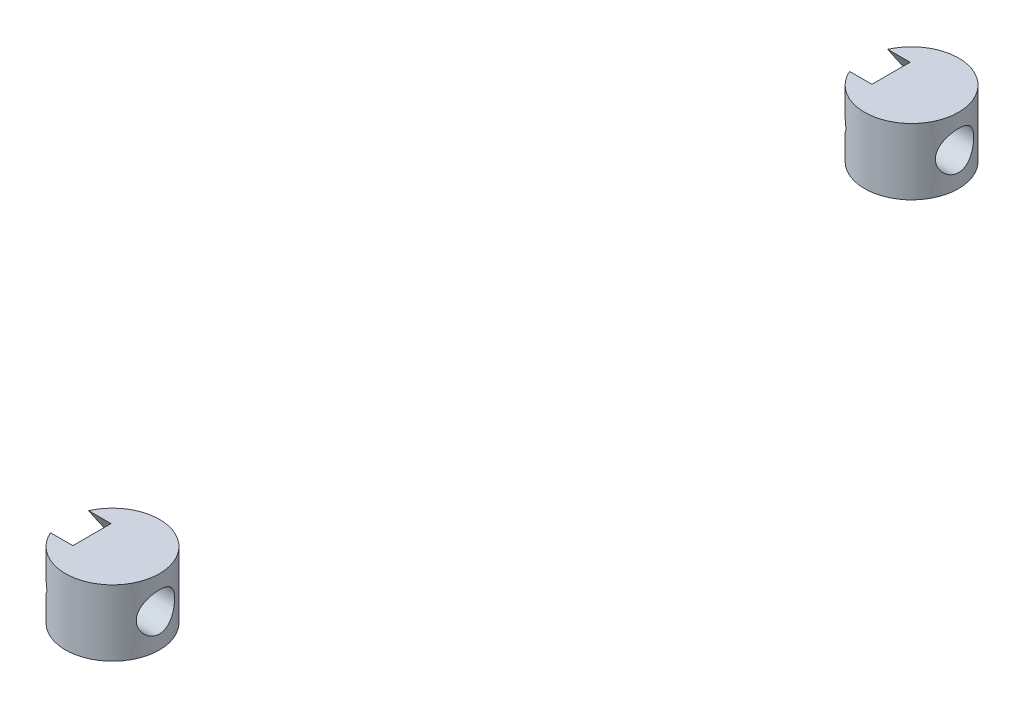
SolidWorks part; units mm, degrees
ref_plane "Front Plane" through (0, 0, 0) normal (0, 0, 1) x (1, 0, 0)
ref_plane "Top Plane" through (0, 0, 0) normal (0, 1, 0) x (1, 0, 0)
ref_plane "Right Plane" through (0, 0, 0) normal (1, 0, 0) x (0, 0, -1)
sketch "Sketch1" plane through (0, 0, 0) normal (0, 1, 0) x (1, 0, 0)
  line L2 (0, -88.9) -> (0, 88.9) construction
  circle A0 centre (0, 76.7) radius 9.025
  circle A1 centre (0, -76.7) radius 9.025
  circle A2 centre (0, 76.7) radius 12.2 construction
  circle A3 centre (0, -76.7) radius 12.2 construction
  point P0 (0, 0)
  point P1 (0, 0)
  point P10 (0, -75.6399)
  point P11 (0, 74.8174)
  dimension "D4" = 18.05
  dimension "D1" = 3.175
  dimension "D2" = 177.8
extrude "Boss-Extrude1" add sketch "Sketch1" along normal blind 12.7
sketch "Sketch2" plane through (0, 0, 0) normal (1, 0, 0) x (0, 0, -1)
  line L0 (-67.675, 12.7) -> (-85.725, 12.7) construction
  line L1 (-67.675, 12.7) -> (-85.725, 12.7) construction
  line L3 (-85.725, 12.7) -> (-85.725, 0) construction
  line L4 (0, 12.7) -> (0, -20.396) construction
  circle A0 centre (-76.7, 6.35) radius 3.675
  circle A1 centre (76.7, 6.35) radius 3.675
  point P4 (-76.7, 12.7)
  point P7 (-85.725, 6.35)
  point P13 (-85.725, 0)
  dimension "D1" = 7.35
extrude "Cut-Extrude1" cut sketch "Sketch2" against normal through all both and the other way through all
ref_plane "Plane1" through (-9.025, 0, 0) normal (-1, 0, 0) x (0, 0, 1)
sketch "Sketch3" plane through (-9.025, 0, 0) normal (-1, 0, 0) x (0, 0, 1)
  line L0 (67.675, 0) -> (85.725, 0) construction
  line L1 (80.3662, 0) -> (84.0323, 6.35)
  line L2 (84.0323, 6.35) -> (80.3662, 12.7)
  line L3 (80.3662, 12.7) -> (73.0338, 12.7)
  line L4 (73.0338, 12.7) -> (69.3677, 6.35)
  line L5 (69.3677, 6.35) -> (73.0338, 0)
  line L6 (73.0338, 0) -> (80.3662, 0)
  line L7 (0, 15.1212) -> (0, -17.7329) construction
  line L8 (-73.0338, 0) -> (-80.3662, 0)
  line L9 (-69.3677, 6.35) -> (-73.0338, 0)
  line L10 (-73.0338, 12.7) -> (-69.3677, 6.35)
  line L11 (-80.3662, 12.7) -> (-73.0338, 12.7)
  line L12 (-84.0323, 6.35) -> (-80.3662, 12.7)
  line L13 (-80.3662, 0) -> (-84.0323, 6.35)
  circle A0 centre (76.7, 6.35) radius 6.35 construction
  circle A1 centre (-76.7, 6.35) radius 6.35 construction
  dimension "D1" = 12.7
extrude "Cut-Extrude2" cut sketch "Sketch3" against normal blind 5.08
